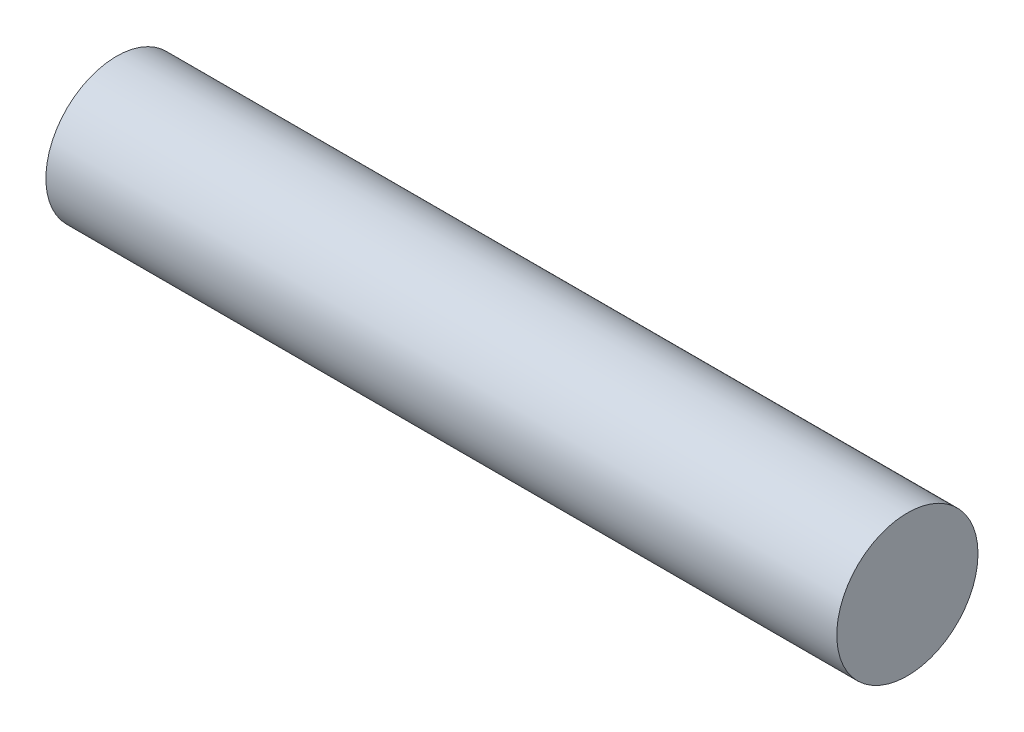
SolidWorks part; units mm, degrees
ref_plane "Front Plane" through (0, 0, 0) normal (0, 0, 1) x (1, 0, 0)
ref_plane "Top Plane" through (0, 0, 0) normal (0, 1, 0) x (1, 0, 0)
ref_plane "Right Plane" through (0, 0, 0) normal (1, 0, 0) x (0, 0, -1)
sketch "Sketch1" plane through (0, 0, 0) normal (1, 0, 0) x (0, 0, -1)
  circle A0 centre (0, 0) radius 3.175
extrude "Boss-Extrude1" add sketch "Sketch1" along normal blind 20.32 and the other way blind 15.24
